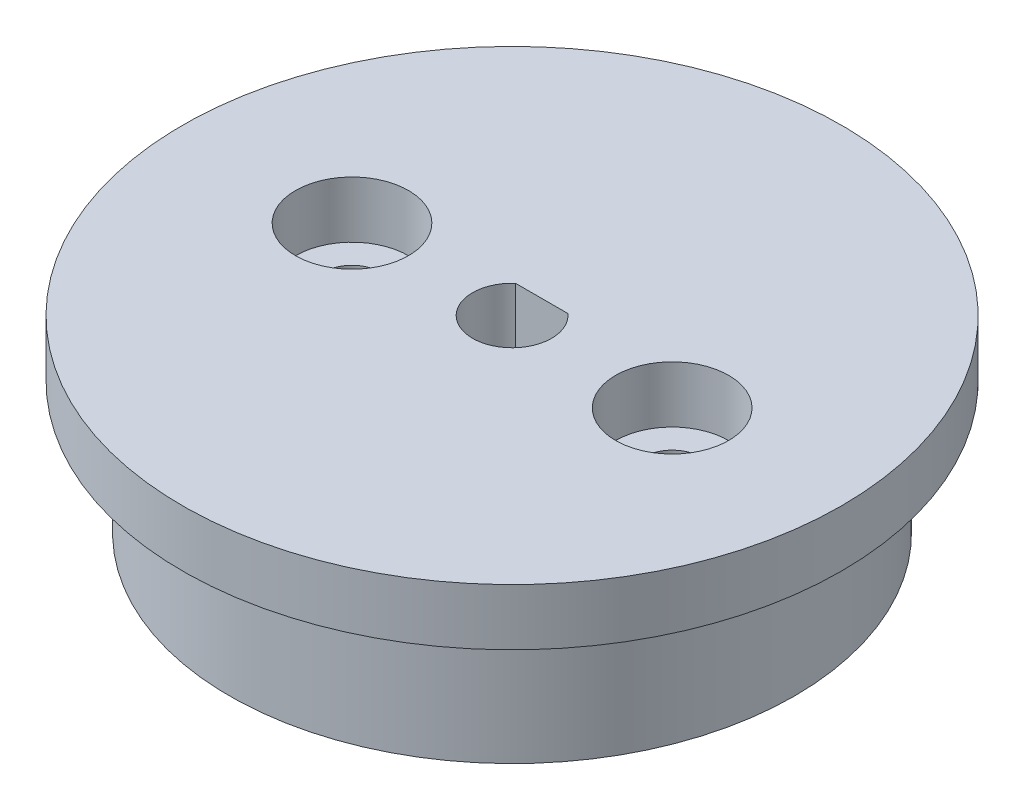
SolidWorks part; units mm, degrees
ref_plane "Plano frontal" through (0, 0, 0) normal (0, 0, 1) x (1, 0, 0)
ref_plane "Plano superior" through (0, 0, 0) normal (0, 1, 0) x (1, 0, 0)
ref_plane "Plano direito" through (0, 0, 0) normal (1, 0, 0) x (0, 0, -1)
sketch "Esboço1" plane through (0, 0, 0) normal (0, 0, 1) x (1, 0, 0)
  line L0 (0, 7) -> (-2.5, 7)
  line L1 (0, 0) -> (15, 0)
  line L2 (0, 0) -> (0, 7)
  line L4 (15, 0) -> (15, 10)
  line L5 (-2.5, 10) -> (15, 10)
  line L8 (-2.5, 7) -> (-2.5, 10)
  point P8 (15, 7)
  point P9 (15, 10)
  point P10 (0, 0)
  point P11 (0, 0)
  dimension "D1" = 15
  dimension "D3" = 3
  dimension "D4" = 2.5
  dimension "D6" = 7
revolve "Revolução2" add sketch "Esboço1" angle 360 about L4
sketch "Esboço2" plane through (0, 0, 0) normal (0, -1, 0) x (-1, 0, 0)
  line L0 (-16.39, 1.5741) -> (-13.61, 1.5741)
  line L2 (0, 0) -> (-6.5, 0)
  line L3 (-30, 0) -> (-23.5, 0)
  arc A1 (-13.61, 1.5741) -> (-16.39, 1.5741) centre (-15, 0) cw
  circle A2 centre (-15, 0) radius 15 construction
  circle A3 centre (-23.5, 0) radius 1.5
  circle A4 centre (-6.5, 0) radius 1.5
  dimension "D1" = 2.78
  dimension "D2" = 2.1
  dimension "D5" = 3
  dimension "D6" = 3
  dimension "D3" = 6.5
  dimension "D4" = 6.5
extrude "Corte-extrusão1" cut sketch "Esboço2" against normal blind 10
sketch "Esboço3" plane through (0, 10, 0) normal (0, 1, 0) x (1, 0, 0)
  circle A0 centre (6.5, 0) radius 3
  circle A1 centre (23.5, 0) radius 3
  dimension "D1" = 6
  dimension "D2" = 6
extrude "Corte-extrusão2" cut sketch "Esboço3" against normal blind 3
